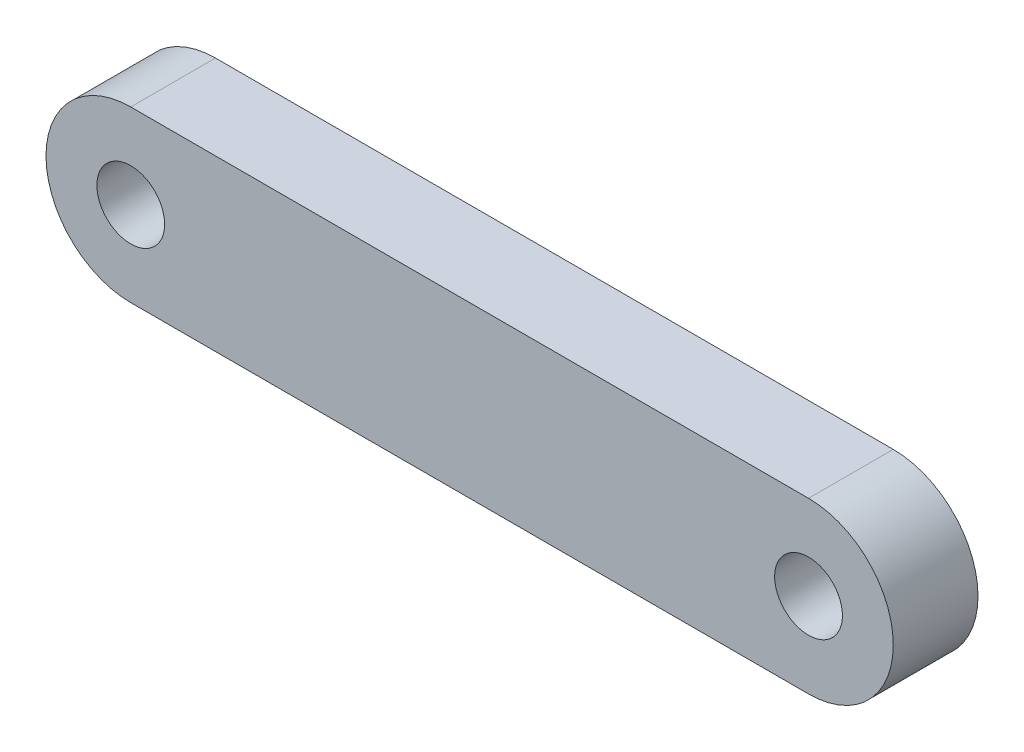
SolidWorks part; units mm, degrees
ref_plane "Plan de face" through (0, 0, 0) normal (0, 0, 1) x (1, 0, 0)
ref_plane "Plan de dessus" through (0, 0, 0) normal (0, 1, 0) x (1, 0, 0)
ref_plane "Plan de droite" through (0, 0, 0) normal (1, 0, 0) x (0, 0, -1)
sketch "Esquisse1" plane through (0, 0, 0) normal (0, 0, 1) x (1, 0, 0)
  line L0 (-20, 0) -> (20, 0) construction
  line L1 (-20, 5) -> (20, 5)
  line L2 (-20, -5) -> (20, -5)
  arc A0 (-20, 5) -> (-20, -5) centre (-20, 0) ccw
  arc A1 (20, -5) -> (20, 5) centre (20, 0) ccw
  circle A2 centre (-20, 0) radius 2
  circle A3 centre (20, 0) radius 2
  point P2 (0, 0)
  dimension "D2" = 5
  dimension "D3" = 4
  dimension "D4" = 4
  dimension "D1" = 40
extrude "Boss.-Extru.1" add sketch "Esquisse1" along normal blind 5
